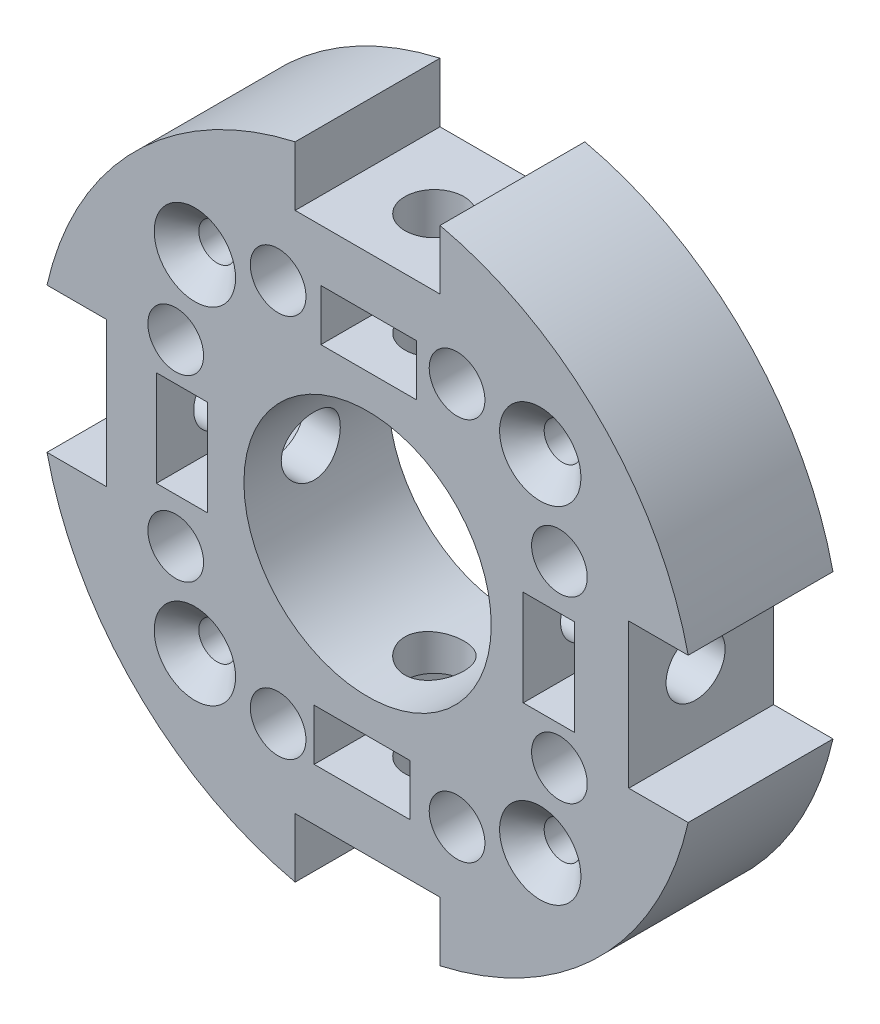
SolidWorks part; units mm, degrees
ref_plane "Plan de face" through (0, 0, 0) normal (0, 0, 1) x (1, 0, 0)
ref_plane "Plan de dessus" through (0, 0, 0) normal (0, 1, 0) x (1, 0, 0)
ref_plane "Plan de droite" through (0, 0, 0) normal (1, 0, 0) x (0, 0, -1)
sketch "Esquisse1" plane through (0, 0, 0) normal (0, 0, 1) x (1, 0, 0)
  line L36 (-18.9562, 4.6) -> (-14.3562, 4.6)
  line L52 (-0.2997, 0.2997) -> (-35355.6388, 35355.6388) construction
  line L54 (0, -1000) -> (0, 49000) construction
  line L60 (6, 23.9414) -> (6, 29.3939) construction
  line L61 (-14.3562, -4) -> (-14.3562, 4.6)
  line L62 (-18.6562, -3.7) -> (-14.6562, -3.7) construction
  line L63 (-18.6562, -3.7) -> (-18.6562, 4.3) construction
  line L64 (-18.6562, 4.3) -> (-14.6562, 4.3) construction
  line L65 (-14.6562, -3.7) -> (-14.6562, 4.3) construction
  line L66 (-18.6562, -3.7) -> (-14.6562, 4.3) construction
  line L67 (-23.9414, -6) -> (-29.3939, -6) construction
  line L68 (-23.9414, -6) -> (-23.9414, 6) construction
  line L69 (-23.9414, 6) -> (-29.3939, 6) construction
  line L71 (-6, 23.9414) -> (6, 23.9414) construction
  line L72 (-6, 23.9414) -> (-6, 29.3939)
  line L73 (-4.2406, 9.094) -> (-21135.1537, 45324.4833) construction
  line L74 (-23.4414, -6.5) -> (-23.4414, 6.5)
  line L75 (-23.4414, 6.5) -> (-28.775, 6.5)
  line L76 (-6.5, 23.4414) -> (-6.5, 28.775)
  line L77 (-18.6562, 4.3) -> (-14.6562, -3.7) construction
  line L78 (-18.9562, -4) -> (-14.3562, -4)
  line L79 (-18.9562, -4) -> (-18.9562, 4.6)
  line L80 (4.4068, 18.7629) -> (4.4068, 14.1629)
  line L81 (-4.1932, 14.1629) -> (4.4068, 14.1629)
  line L82 (-4.1932, 18.7629) -> (-4.1932, 14.1629)
  line L83 (-4.1932, 18.7629) -> (4.4068, 18.7629)
  line L84 (18.5697, -4.6) -> (13.9697, -4.6)
  line L85 (13.9697, 4) -> (13.9697, -4.6)
  line L86 (18.5697, 4) -> (13.9697, 4)
  line L87 (18.5697, 4) -> (18.5697, -4.6)
  line L88 (-4.7932, -18.7629) -> (-4.7932, -14.1629)
  line L89 (3.8068, -14.1629) -> (-4.7932, -14.1629)
  line L90 (3.8068, -18.7629) -> (3.8068, -14.1629)
  line L91 (3.8068, -18.7629) -> (-4.7932, -18.7629)
  line L92 (23.9414, -6) -> (29.3939, -6) construction
  line L93 (23.9414, 6) -> (23.9414, -6) construction
  line L94 (23.9414, 6) -> (29.3939, 6) construction
  line L95 (-6, -23.9414) -> (-6, -29.3939) construction
  line L96 (6, -23.9414) -> (-6, -23.9414) construction
  line L97 (6, -23.9414) -> (6, -29.3939) construction
  line L98 (-6.5, 23.4414) -> (6.5, 23.4414)
  line L99 (6.5, 23.4414) -> (6.5, 28.775)
  line L100 (23.4414, 6.5) -> (28.775, 6.5)
  line L101 (23.4414, 6.5) -> (23.4414, -6.5)
  line L102 (23.4414, -6.5) -> (28.775, -6.5)
  line L103 (6.5, -23.4414) -> (6.5, -28.775)
  line L104 (6.5, -23.4414) -> (-6.5, -23.4414)
  line L105 (-6.5, -23.4414) -> (-6.5, -28.775)
  line L106 (-23.4414, -6.5) -> (-28.775, -6.5)
  circle A1 centre (0, 0) radius 11.1
  circle A2 centre (-15.5, 15.5) radius 1.65
  circle A3 centre (15.5, 15.5) radius 1.65
  circle A4 centre (15.5, -15.5) radius 1.65
  circle A5 centre (-15.5, -15.5) radius 1.65
  arc A18 (-29.3939, -6) -> (-6, -29.3939) centre (0, 0) ccw construction
  circle A21 centre (-8.0297, 17.2198) radius 2.5
  arc A23 (-6, 29.3939) -> (-29.3939, 6) centre (0, 0) ccw construction
  arc A24 (29.3939, 6) -> (6, 29.3939) centre (0, 0) ccw construction
  arc A25 (6, -29.3939) -> (29.3939, -6) centre (0, 0) ccw construction
  circle A26 centre (8.0297, 17.2198) radius 2.5
  circle A27 centre (17.2198, 8.0297) radius 2.5
  circle A28 centre (17.2198, -8.0297) radius 2.5
  circle A29 centre (8.0297, -17.2198) radius 2.5
  circle A30 centre (-8.0297, -17.2198) radius 2.5
  circle A31 centre (-17.2198, -8.0297) radius 2.5
  circle A32 centre (-17.2198, 8.0297) radius 2.5
  arc A33 (-6.5, 28.775) -> (-28.775, 6.5) centre (0, 0) ccw
  arc A34 (28.775, 6.5) -> (6.5, 28.775) centre (0, 0) ccw
  arc A35 (6.5, -28.775) -> (28.775, -6.5) centre (0, 0) ccw
  arc A36 (-28.775, -6.5) -> (-6.5, -28.775) centre (0, 0) ccw
  point P1 (-27.9414, 0)
  point P22 (0, 0)
  point P32 (0, 0)
  point P33 (0, 0)
  point P39 (-16.6562, 0.3)
  point P73 (0, 0)
  point P75 (0, 0)
  point P90 (0, 0)
  dimension "D2" = 22.2
  dimension "D7" = 3.3
  dimension "D14" = 0.5
  dimension "D18" = 8
  dimension "D6" = 5.4525
  dimension "D15" = 5
  dimension "D4" = 60
  dimension "D11" = 4
  dimension "D3" = 12
  dimension "D5" = 21.9203
  dimension "D9" = 0.3
  dimension "D10" = 4
  dimension "D16" = 45
  dimension "D17" = 19
  dimension "D19" = 4
  dimension "D12" = 25
  dimension "D8" = 4
  dimension "D13" = 4
extrude "Boss.-Extru.1" add sketch "Esquisse1" along normal blind 13
chamfer "Chanfrein1" distance 2 angle 45 4 edges at (-13.85, -15.5, 13) (17.15, -15.5, 13) (17.15, 15.5, 13) (-13.85, 15.5, 13)
sketch "Esquisse2" plane through (-14.3562, 0, 0) normal (-1, 0, 0) x (0, 0, 1)
  line L1 (13, -6.5) -> (13, 6.5) construction
  circle A0 centre (7, 0) radius 2.65
  dimension "D1" = 5.3
  dimension "D2" = 6
extrude "Enlèv. mat.-Extru.1" cut sketch "Esquisse2" against normal up to next and the other way through all
pattern_circular "Répétition circulaire1" count 4 over 360 of "Enlèv. mat.-Extru.1"
